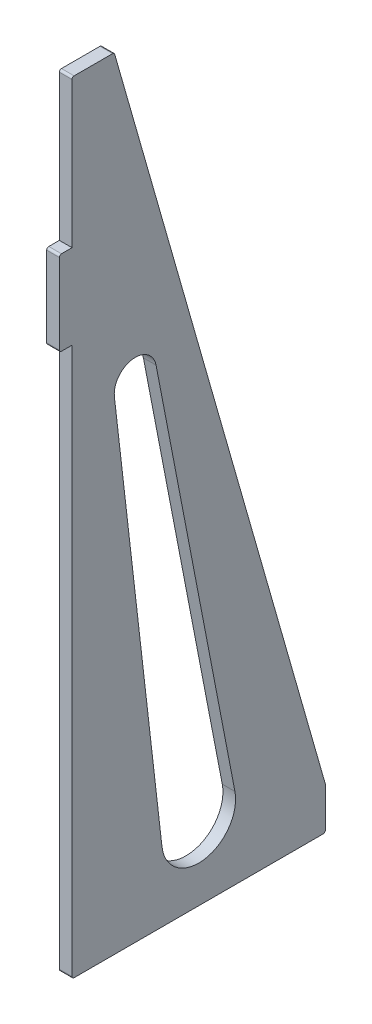
SolidWorks part; units mm, degrees
material "Beech"
ref_plane "Спереди" through (0, 0, 0) normal (0, 0, 1) x (1, 0, 0)
ref_plane "Сверху" through (0, 0, 0) normal (0, 1, 0) x (1, 0, 0)
ref_plane "Справа" through (0, 0, 0) normal (1, 0, 0) x (0, 0, -1)
sketch "Sketch1" plane through (0, 0, 0) normal (1, 0, 0) x (0, 0, -1)
  line L0 (0, 0) -> (0, 370)
  line L1 (0, 370) -> (26, 370)
  line L2 (26, 370) -> (126, 20)
  line L3 (126, 20) -> (126, 0)
  line L4 (126, 0) -> (0, 0)
  dimension "D1" = 126
  dimension "D2" = 370
  dimension "D3" = 20
  dimension "D4" = 26
extrude "corner" add sketch "Sketch1" along normal blind 6
sketch "Sketch2" plane through (6, 0, 0) normal (1, 0, 0) x (0, 0, -1)
  line L0 (6, 370) -> (6, 300)
  line L1 (26, 370) -> (0, 370) construction
  line L2 (6, 300) -> (0, 300)
  line L3 (0, 370) -> (0, 0) construction
  line L4 (0, 300) -> (0, 370)
  line L5 (0, 370) -> (6, 370)
  line L6 (0, 260) -> (6, 260)
  line L7 (6, 260) -> (6, 0)
  line L8 (0, 0) -> (126, 0) construction
  line L9 (6, 0) -> (0, 0)
  line L10 (0, 0) -> (0, 260)
  dimension "D1" = 6
  dimension "D2" = 40
  dimension "D4" = 260
extrude "mount" cut sketch "Sketch2" against normal blind 10
fillet "Fillet1" radius 1 7 edges at (3, 20, -126) (3, 0, -126) (3, 0, -6) (3, 260, 0) (3, 300, 0) (3, 370, -26) (3, 370, -6)
sketch "Sketch3" plane through (6, 0, 0) normal (1, 0, 0) x (0, 0, -1)
  line L0 (26.0656, 228.8562) -> (48.6148, 32.9984)
  line L1 (45.8188, 231.8952) -> (83.1828, 38.3166)
  line L2 (126, 1) -> (126, 19.8599) construction
  line L3 (7, 0) -> (125, 0) construction
  line L4 (25.2457, 370) -> (7, 370) construction
  line L5 (6, 300) -> (6, 369) construction
  arc A0 (83.1828, 38.3166) -> (48.6148, 32.9984) centre (66, 35) cw
  arc A1 (26.0656, 228.8562) -> (45.8188, 231.8952) centre (36, 230) cw
  dimension "D1" = 17.5
  dimension "D2" = 60
  dimension "D3" = 35
  dimension "D4" = 140
  dimension "D5" = 10
  dimension "D6" = 30
extrude "lite" cut sketch "Sketch3" against normal through all
